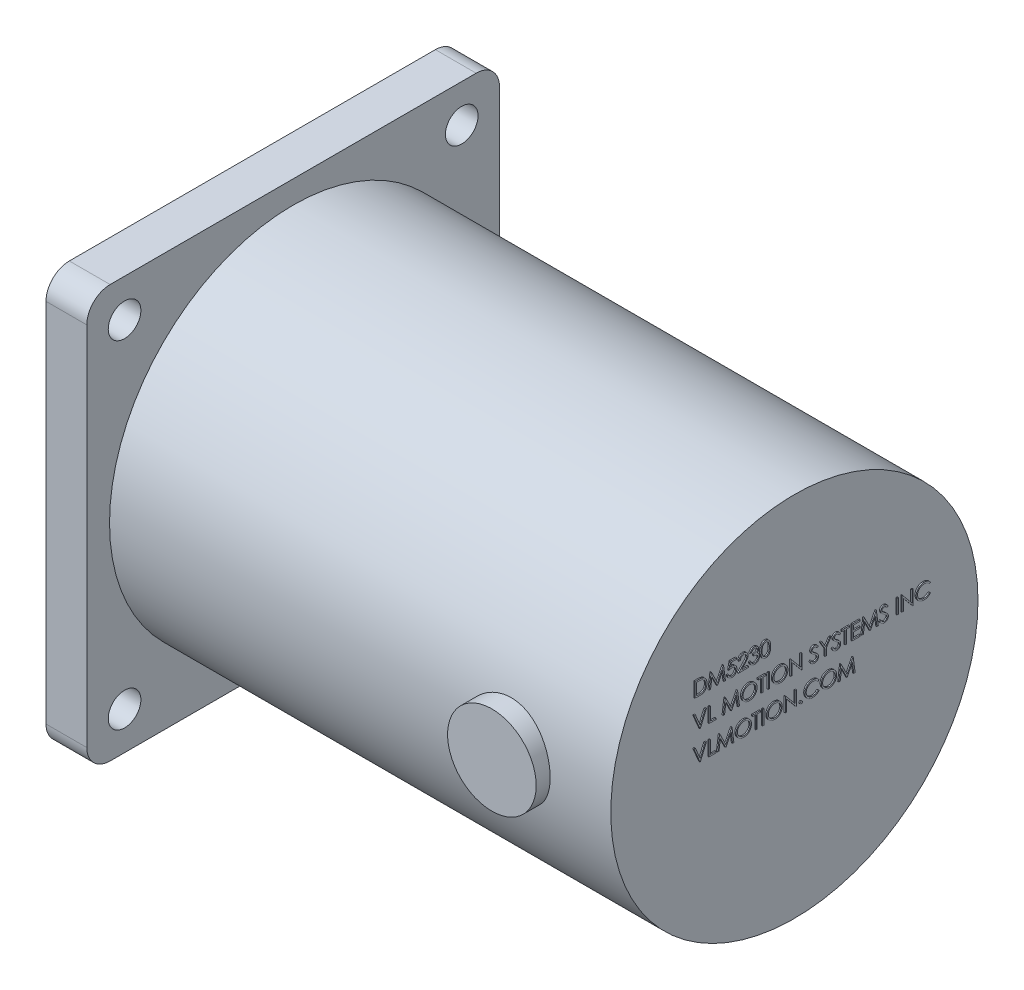
SolidWorks part; units mm, degrees
ref_plane "Front Plane" through (0, 0, 0) normal (0, 0, 1) x (1, 0, 0)
ref_plane "Top Plane" through (0, 0, 0) normal (0, 1, 0) x (1, 0, 0)
ref_plane "Right Plane" through (0, 0, 0) normal (1, 0, 0) x (0, 0, -1)
sketch "Sketch1" plane through (0, 0, 0) normal (1, 0, 0) x (0, 0, -1)
  circle A0 centre (0, 0) radius 40.005
  dimension "D1" = 80.01
extrude "Boss-Extrude1" add sketch "Sketch1" against normal blind 109.22
sketch "Sketch2" plane through (-109.22, 0, 0) normal (-1, 0, 0) x (0, 0, 1)
  line L1 (-44.958, 44.958) -> (44.958, 44.958)
  line L2 (-44.958, 44.958) -> (-44.958, -44.958)
  line L3 (-44.958, -44.958) -> (44.958, -44.958)
  line L4 (44.958, 44.958) -> (44.958, -44.958)
  line L5 (-44.958, 44.958) -> (44.958, -44.958) construction
  line L6 (-44.958, -44.958) -> (44.958, 44.958) construction
  point P0 (0, 0)
  dimension "D1" = 89.916
  dimension "D2" = 89.916
extrude "Boss-Extrude2" add sketch "Sketch2" along normal blind 8.89
fillet "Fillet1" radius 5.08 4 edges at (-113.665, 44.958, -44.958) (-113.665, -44.958, -44.958) (-113.665, -44.958, 44.958) (-113.665, 44.958, 44.958)
sketch "Sketch3" plane through (-118.11, 0, 0) normal (-1, 0, 0) x (0, 0, 1)
  circle A0 centre (0, 0) radius 41.529
  dimension "D1" = 83.058
extrude "Boss-Extrude3" add sketch "Sketch3" along normal blind 2
sketch "Sketch4" plane through (-118.11, 0, 0) normal (-1, 0, 0) x (0, 0, 1)
  line L0 (0, 0) -> (36.7292, 36.7292) construction
  line L1 (-44.958, 0) -> (44.958, 0) construction
  line L2 (-44.958, 39.878) -> (-44.958, -39.878) construction
  line L3 (44.958, -39.878) -> (44.958, 39.878) construction
  circle A0 centre (36.7292, 36.7292) radius 3.556
  dimension "D3" = 7.112
  dimension "D1" = 45
  dimension "D2" = 51.943
extrude "Cut-Extrude4" cut sketch "Sketch4" against normal up to next
pattern_circular "CirPattern1" count 4 over 360 about axis through (0, 0, 0) along (1, 0, 0) of "Cut-Extrude4"
sketch "Sketch6" plane through (-120.11, 0, 0) normal (-1, 0, 0) x (0, 0, 1)
  circle A0 centre (0, 0) radius 5
  dimension "D1" = 10
extrude "Boss-Extrude4" add sketch "Sketch6" along normal blind 29.5
ref_plane "Plane1" through (0, 2.6604, 0) normal (0, 1, 0) x (1, 0, 0)
sketch "Sketch7" plane through (0, 2.6604, 0) normal (0, 1, 0) x (1, 0, 0)
  line L0 (-149.61, 0) -> (-128.0117, 0) construction
  line L1 (-149.61, 5) -> (-149.61, -5) construction
  line L2 (-149.61, 2.0312) -> (-128.0127, 2.0312)
  line L3 (-149.61, -1.9688) -> (-127.512, -1.9688)
  line L4 (-149.61, 2.0312) -> (-149.61, -1.9688)
  arc A1 (-127.512, -1.9688) -> (-128.0127, 2.0312) centre (-128.0117, 0) ccw
  point P5 (-139.11, 0)
  dimension "D1" = 4
  dimension "D2" = 22.098
extrude "Boss-Extrude5" add sketch "Sketch7" along normal blind 4
ref_plane "Plane2" through (0, 0, 40.005) normal (0, 0, 1) x (1, 0, 0)
sketch "Sketch8" plane through (0, 0, 40.005) normal (0, 0, 1) x (1, 0, 0)
  line L0 (0, 0) -> (-22.86, 0) construction
  circle A0 centre (-22.86, 0) radius 9.652
  dimension "D2" = 19.304
  dimension "D1" = 22.86
extrude "Boss-Extrude6" add sketch "Sketch8" along normal blind 3.048 and the other way up to surface (3.048 mm away)
mirror "Mirror1" about plane through (0, 0, 0) normal (0, 0, 1) of "Boss-Extrude6"
sketch "Sketch10" plane through (0, 0, 0) normal (1, 0, 0) x (0, 0, -1)
  text T0 "DM5230\r\nVL MOTION SYSTEMS INC\r\nVLMOTION.COM"
  point P1 (-20.4126, 20.5725)
extrude "Boss-Extrude7" add sketch "Sketch10" along normal blind 0.254
